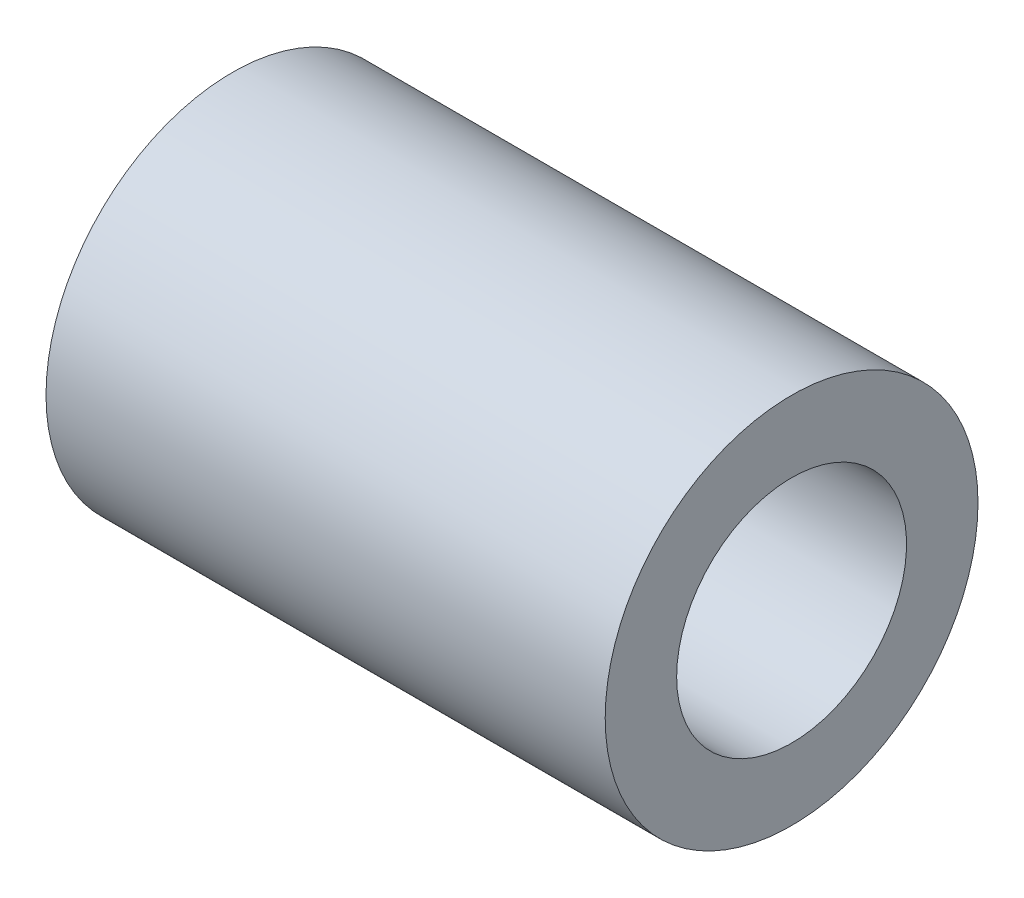
SolidWorks part; units mm, degrees
material "Brass"
ref_plane "Front Plane" through (0, 0, 0) normal (0, 0, 1) x (1, 0, 0)
ref_plane "Top Plane" through (0, 0, 0) normal (0, 1, 0) x (1, 0, 0)
ref_plane "Right Plane" through (0, 0, 0) normal (1, 0, 0) x (0, 0, -1)
sketch "Sketch1" plane through (0, 0, 0) normal (0, 0, 1) x (1, 0, 0)
  line L0 (0, 0) -> (0, 49000) construction
  line L2 (0, 3) -> (9, 3)
  line L3 (9, 3) -> (9, 1.85)
  line L4 (9, 1.85) -> (0, 1.85)
  line L6 (-1000, 0) -> (49000, 0) construction
  line L7 (0, -1000) -> (0, 0) construction
  line L11 (0, 3) -> (0, 1.85)
  dimension "D1" = 9
  dimension "D2" = 6
  dimension "D5" = 3.7
  dimension "D6" = 1.15
revolve "Revolve1" add sketch "Sketch1" angle 360 about L6
